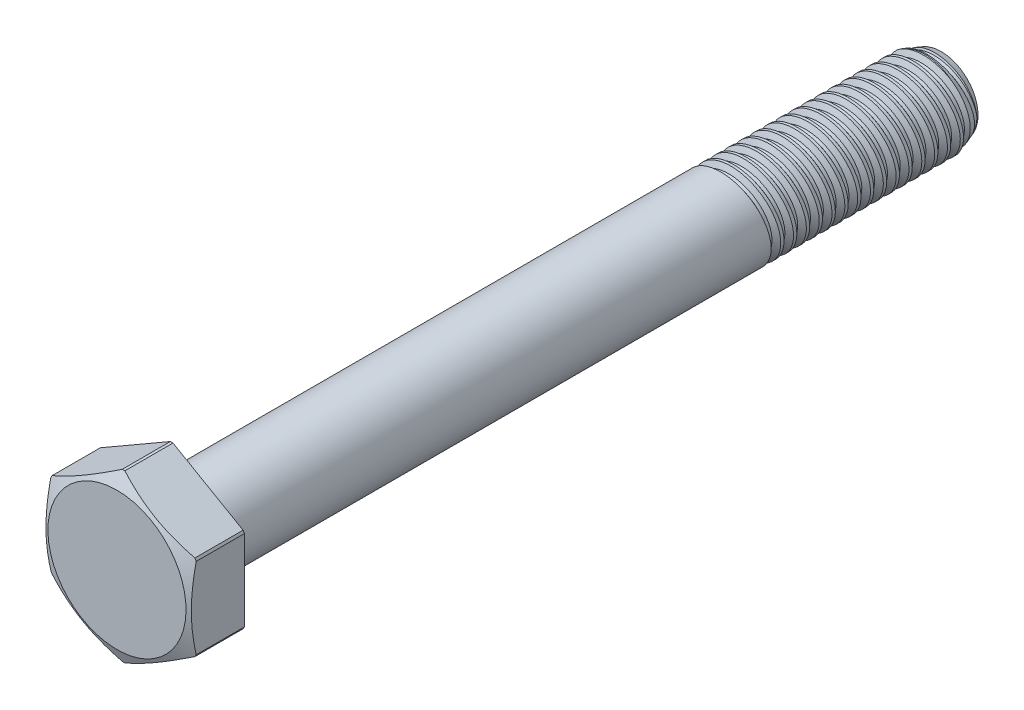
SolidWorks part; units mm, degrees
material "Alloy Steel"
ref_plane "Front" through (0, 0, 0) normal (0, 0, 1) x (1, 0, 0)
ref_plane "Top" through (0, 0, 0) normal (0, 1, 0) x (1, 0, 0)
ref_plane "Right" through (0, 0, 0) normal (1, 0, 0) x (0, 0, -1)
sketch "Sketch1" plane through (0, 0, 0) normal (1, 0, 0) x (0, 0, -1)
  line L0 (0, 0) -> (-6.4, 0) construction
  line L1 (0, 0) -> (90, 0)
  line L2 (0, 0) -> (0, 5)
  line L3 (0, 5) -> (90, 5)
  line L4 (90, 0) -> (90, 5)
  line L5 (0, -5) -> (90, -5) construction
  dimension "D1" = 90
  dimension "Thread Dia" = 10
  dimension "Length" = 90
  dimension "Head Height" = 6.4
revolve "Revolve1" add sketch "Sketch1" angle 360 about L0
ref_plane "Plane1" through (0, 0, 6.4) normal (0, 0, 1) x (1, 0, 0)
sketch "Sketch2" plane through (0, 0, 0) normal (1, 0, 0) x (0, 0, -1)
  line L0 (64, 5) -> (64, -5) construction
  line L1 (64, -5) -> (65.5, -5) construction
  line L2 (65.5, -5) -> (64, 5) construction
  line L3 (64, 5) -> (64.1854, 5.0278) construction
  line L4 (64.1854, 5.0278) -> (65.4834, 5.2225)
  line L5 (65.4834, 5.2225) -> (65.1403, 4.3501)
  line L6 (65.1403, 4.3501) -> (64.7694, 4.2944)
  line L7 (64.7694, 4.2944) -> (64.1854, 5.0278)
  line L8 (64.9549, 4.3222) -> (64.8344, 5.1252) construction
  line L9 (0, -5) -> (90, -5) construction
  line L10 (0, 5) -> (90, 5) construction
  line L11 (90, 0) -> (90, 5) construction
  line L12 (64.8532, 5) -> (66.3532, -5) construction
  line L13 (64, -0.2405) -> (67.2064, 0.2405) construction
  point P19 (65.6032, 0)
  dimension "D1" = 60
  dimension "Thread Pitch" = 1.5
  dimension "D2" = 0.1875
  dimension "D3" = 0.375
  dimension "D4" = 1.5
  dimension "Min Thread Length" = 26
revolve "Cut-Revolve1" cut sketch "Sketch2" angle 360 about L13
sketch "Sketch3" plane through (0, 0, 0) normal (1, 0, 0) x (0, 0, -1)
  line L0 (90, 4.2944) -> (88.0615, 5)
  line L1 (88.0615, 5) -> (90, 5)
  line L2 (90, 5) -> (90, 4.2944)
  line L3 (0, 5) -> (90, 5) construction
  line L4 (90, 0) -> (90, 5) construction
  line L5 (88.0615, 0) -> (0, 0) construction
  line L6 (88.0615, 5) -> (88.0615, -5) construction
  line L7 (0, -5) -> (90, -5) construction
  dimension "D1" = 20
  dimension "D2" = 10
revolve "Cut-Revolve2" cut sketch "Sketch3" angle 360 about L5
pattern_linear "LPattern1" count 17 spacing 1.5 along (0, 0, -1) of "Cut-Revolve1"
sketch "Sketch4" plane through (0, 0, 0) normal (0, 0, 1) x (1, 0, 0)
  line L1 (0, 9.815) -> (-8.5, 4.9075)
  line L2 (-8.5, 4.9075) -> (-8.5, -4.9075)
  line L3 (-8.5, -4.9075) -> (0, -9.815)
  line L4 (0, -9.815) -> (8.5, -4.9075)
  line L5 (8.5, -4.9075) -> (8.5, 4.9075)
  line L6 (8.5, 4.9075) -> (0, 9.815)
  circle A0 centre (0, 0) radius 8.5 construction
  circle A1 centre (0, 0) radius 8.5 construction
  dimension "Head Dia" = 17
extrude "Extrude1" add sketch "Sketch4" along normal up to surface (6.4 mm away) up to plane "Plane1"
sketch "Sketch9" plane through (0, 0, 0) normal (1, 0, 0) x (0, 0, -1)
  line L0 (-6.4, 8.075) -> (-5.6292, 9.728)
  line L1 (0, 9.815) -> (-6.4, 9.815)
  line L2 (-6.4, 9.815) -> (-6.4, 8.075)
  line L3 (0, 0) -> (-6.4, 0) construction
  line L4 (-6.4, 9.815) -> (0, 9.815) construction
  line L5 (-6.4, 4.9075) -> (-6.4, 9.815) construction
  line L6 (-5.6292, 9.728) -> (0, 9.728)
  line L10 (0, 9.728) -> (0, 9.815)
  line L11 (0, 4.9075) -> (0, 9.815) construction
  dimension "D2" = 16.15
  dimension "D4" = 0.087
  dimension "D1" = 25
  dimension "D3" = 1.74
  dimension "D5" = 6.4
  dimension "D6" = 90
revolve "Cut-Revolve3" cut sketch "Sketch9" angle 360 about L3
equation "\"D2@Sketch2\"=\"Thread Pitch@Sketch2\"/8"
equation "\"D3@Sketch2\"=\"Thread Pitch@Sketch2\"/4"
equation "\"D4@Sketch2\"=\"Thread Pitch@Sketch2\""
equation "\"D3@LPattern1\"=\"Thread Pitch@Sketch2\""
equation "\"D1@LPattern1\"=\"Min Thread Length@Sketch2\"/\"Thread Pitch@Sketch2\""
equation "\"D2@Sketch9\"=\"Head Dia@Sketch4\"*.95"
equation "\"D4@Sketch9\"=\"D3@Sketch9\"/20"
